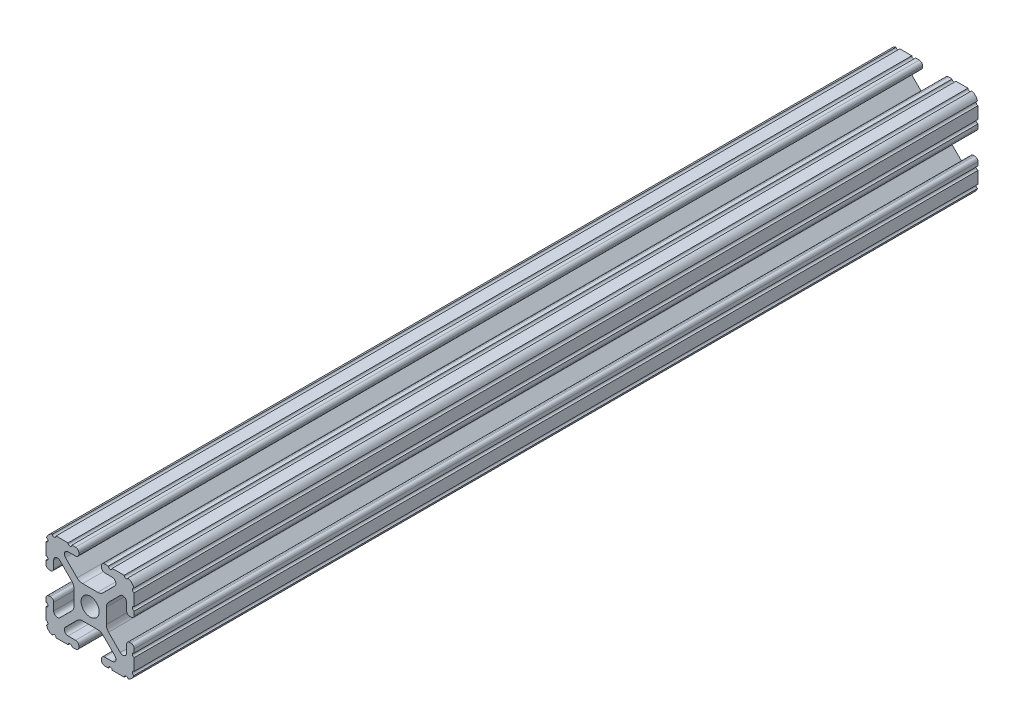
SolidWorks part; units mm, degrees
ref_plane "Front Plane" through (0, 0, 0) normal (0, 0, 1) x (1, 0, 0)
ref_plane "Top Plane" through (0, 0, 0) normal (0, 1, 0) x (1, 0, 0)
ref_plane "Right Plane" through (0, 0, 0) normal (1, 0, 0) x (0, 0, -1)
sketch "Sketch2" plane through (0, 0, 0) normal (0, 0, 1) x (1, 0, 0)
  line L0 (0, 12.7) -> (0, -12.7) construction
  line L1 (-12.7, 0) -> (12.7, 0) construction
  line L2 (3.2512, -12.7) -> (12.7, -12.7)
  line L3 (12.7, -12.7) -> (12.7, -3.2512)
  line L4 (3.2512, -12.7) -> (3.2512, -10.4902)
  line L5 (3.2512, -10.4902) -> (8.9276, -10.4902)
  line L6 (8.9276, -10.4902) -> (3.0856, -4.6482)
  line L7 (0, 0) -> (12.7, -12.7) construction
  line L8 (12.7, -3.2512) -> (10.4902, -3.2512)
  line L9 (10.4902, -3.2512) -> (10.4902, -8.9276)
  line L10 (10.4902, -8.9276) -> (4.6482, -3.0856)
  circle A0 centre (0, 0) radius 2.6035
  arc A1 (6.3485, -10.4902) -> (7.1039, -8.6665) centre (6.3485, -9.4219) ccw construction
  point P8 (0, -4.6482)
  dimension "Center Hole Diameter" = 5.207
  dimension "Rail Height" = 25.4
  dimension "Rail Width" = 25.4
  dimension "T-Slot Width" = 6.5024
  dimension "Slot Inner Width" = 14.8336
  dimension "Thickness" = 2.2098
  dimension "Slot Depth" = 5.842
  dimension "D1" = 2.2098
sketch "Sketch3" plane through (0, 0, 0) normal (1, 0, 0) x (0, 0, -1)
  line L0 (-121.4348, -12.7) -> (121.4348, -12.7) construction
  line L1 (-96.0348, 0) -> (96.0348, 0) construction
  line L3 (121.4348, 0) -> (-121.4348, 0) construction
sketch "Sketch4" plane through (0, 0, 0) normal (0, 0, 1) x (1, 0, 0)
  line L0 (4.1904, -12.7) -> (10.1173, -12.7)
  line L1 (3.2512, -12.7) -> (12.7, -12.7) construction
  line L2 (3.2512, -12.7) -> (3.2512, -10.4902) construction
  line L3 (3.2512, -10.4902) -> (8.9276, -10.4902) construction
  line L4 (3.2512, -11.4294) -> (3.2512, -11.7608)
  line L5 (4.1904, -10.4902) -> (6.3485, -10.4902)
  line L6 (0, -4.6482) -> (2.164, -4.6482)
  line L7 (8.9276, -10.4902) -> (3.0856, -4.6482) construction
  line L8 (3.7373, -5.2999) -> (7.1039, -8.6665)
  line L9 (12.7, -12.7) -> (12.7, -3.2512) construction
  line L10 (10.4902, -8.9276) -> (4.6482, -3.0856) construction
  line L11 (10.4902, -3.2512) -> (10.4902, -8.9276) construction
  line L12 (10.4902, -6.3485) -> (10.4902, -4.1904)
  line L13 (12.7, -3.2512) -> (10.4902, -3.2512) construction
  line L14 (11.4294, -3.2512) -> (11.7608, -3.2512)
  line L15 (12.7, -4.1904) -> (12.7, -10.1173)
  line L16 (8.6665, -7.1039) -> (5.2999, -3.7373)
  line L17 (4.6482, 0) -> (4.6482, -2.164)
  line L18 (-12.7, 0) -> (12.7, 0) construction
  line L19 (0, -4.6482) -> (0, -2.6035)
  line L20 (0, 12.7) -> (0, -12.7) construction
  line L21 (4.6482, 0) -> (2.6035, 0)
  arc A0 (3.2512, -11.7608) -> (4.1904, -12.7) centre (4.1904, -11.7608) ccw
  arc A2 (3.2512, -11.4294) -> (4.1904, -10.4902) centre (4.1904, -11.4294) cw
  arc A3 (6.3485, -10.4902) -> (7.1039, -8.6665) centre (6.3485, -9.4219) ccw
  arc A4 (2.164, -4.6482) -> (3.7373, -5.2999) centre (2.164, -6.8732) cw
  arc A5 (10.1173, -12.7) -> (12.7, -10.1173) centre (10.1173, -10.1173) ccw
  arc A6 (8.6665, -7.1039) -> (10.4902, -6.3485) centre (9.4219, -6.3485) ccw
  arc A7 (10.4902, -4.1904) -> (11.4294, -3.2512) centre (11.4294, -4.1904) cw
  arc A8 (11.7608, -3.2512) -> (12.7, -4.1904) centre (11.7608, -4.1904) cw
  arc A9 (5.2999, -3.7373) -> (4.6482, -2.164) centre (6.8732, -2.164) cw
  circle A10 centre (0, 0) radius 2.6035 construction
  arc A11 (0, -2.6035) -> (2.6035, 0) centre (0, 0) ccw
  dimension "D1" = 2.5827
  dimension "D2" = 2.225
  dimension "D3" = 0.9392
extrude "Boss-Extrude1" add sketch "Sketch4" along normal up to vertex (121.4348 mm away) from vertex at -121.4348 starting at point (0, -12.7, -121.4348)
sketch "Sketch5" plane through (0, 0, 0) normal (0, 0, 1) x (1, 0, 0)
  line L0 (3.2512, -12.7) -> (12.7, -12.7) construction
  line L1 (4.1904, -10.4902) -> (6.3485, -10.4902) construction
  line L3 (0, 0) -> (12.7, -12.7) construction
  line L4 (6.3485, -10.4902) -> (6.3485, -12.7) construction
  line L5 (8.9276, -10.4902) -> (3.0856, -4.6482) construction
  circle A0 centre (10.3562, -12.7) radius 0.5524
  circle A1 centre (5.796, -12.7) radius 0.5524
  circle A2 centre (12.7, -10.3562) radius 0.5524
  circle A3 centre (12.7, -5.796) radius 0.5524
  point P10 (5.2694, -10.4902)
  point P12 (9.4219, -6.3485)
  dimension "D1" = 1.1049
extrude "Cut-Extrude1" cut sketch "Sketch5" against normal through all both and the other way through all
mirror "Mirror1" about plane through (0, 0, 0) normal (1, 0, 0) of bodies 137 134
mirror "Mirror2" about plane through (0, 0, 0) normal (0, 1, 0) of bodies 135
equation "\"D1@Sketch2\"=\"Thickness@Sketch2\""
equation "\"D2@Sketch4\"=\"Slot Inner Width@Sketch2\"*0.15"
equation "\"D1@Sketch4\"=\"D3@Sketch4\"*2.75"
equation "\"D3@Sketch4\"=\"Thickness@Sketch2\"*0.425"
equation "\"D1@Sketch5\"=\"Thickness@Sketch2\"*0.5"
equation "\"D1@Boss-Extrude1\"=\"Length@Sketch3\""
